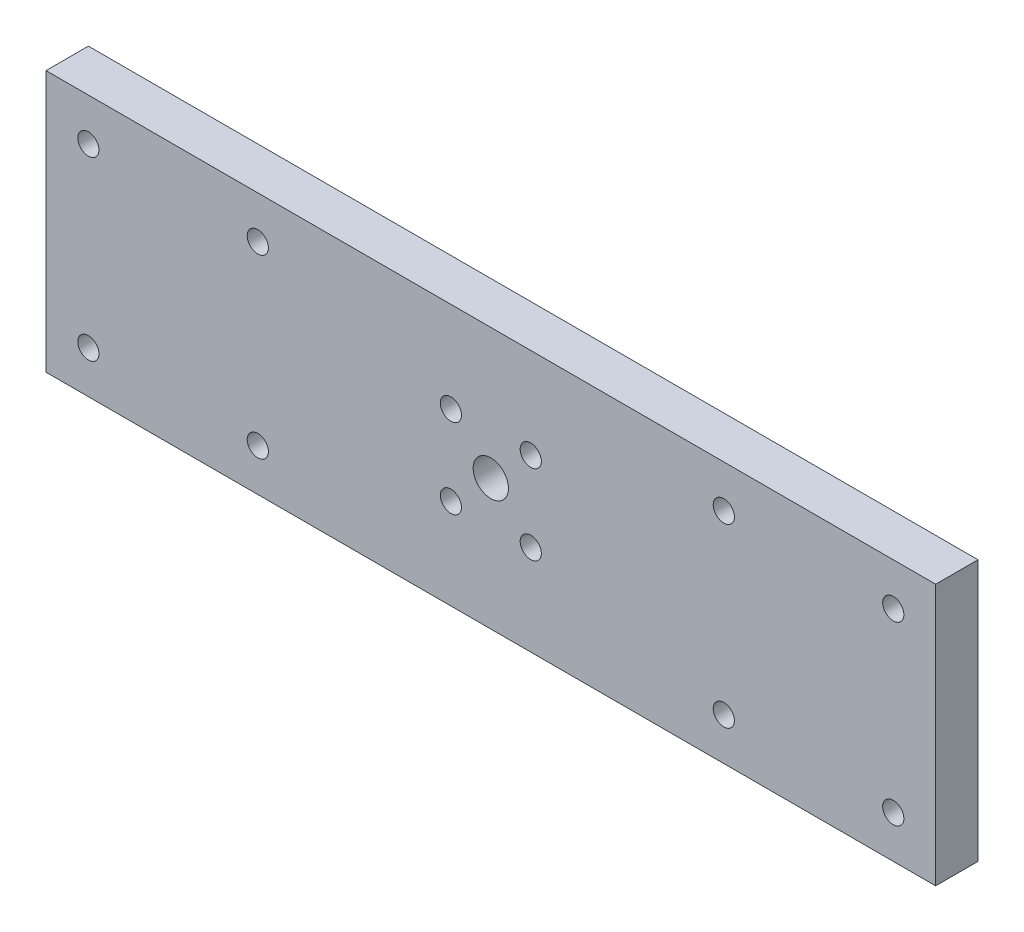
SolidWorks part; units mm, degrees
ref_plane "前视基准面" through (0, 0, 0) normal (0, 0, 1) x (1, 0, 0)
ref_plane "上视基准面" through (0, 0, 0) normal (0, 1, 0) x (1, 0, 0)
ref_plane "右视基准面" through (0, 0, 0) normal (1, 0, 0) x (0, 0, -1)
sketch "草图1" plane through (0, 0, 0) normal (0, 0, 1) x (1, 0, 0)
  line L1 (-63, 18.5) -> (63, 18.5)
  line L2 (-63, 18.5) -> (-63, -18.5)
  line L3 (-63, -18.5) -> (63, -18.5)
  line L4 (63, 18.5) -> (63, -18.5)
  line L5 (-63, 18.5) -> (63, -18.5) construction
  line L6 (-63, -18.5) -> (63, 18.5) construction
  line L7 (-57, 12.5) -> (-33, 12.5)
  line L8 (-57, 12.5) -> (-57, -12.5)
  line L9 (-57, -12.5) -> (-33, -12.5)
  line L10 (-33, 12.5) -> (-33, -12.5)
  line L11 (-57, 12.5) -> (-33, -12.5) construction
  line L12 (-57, -12.5) -> (-33, 12.5) construction
  line L13 (33, 12.5) -> (57, 12.5)
  line L14 (33, 12.5) -> (33, -12.5)
  line L15 (33, -12.5) -> (57, -12.5)
  line L16 (57, 12.5) -> (57, -12.5)
  line L17 (33, 12.5) -> (57, -12.5) construction
  line L18 (33, -12.5) -> (57, 12.5) construction
  line L19 (-10, 10) -> (10, 10)
  line L20 (-10, 10) -> (-10, -10)
  line L21 (-10, -10) -> (10, -10)
  line L22 (10, 10) -> (10, -10)
  line L23 (-10, 10) -> (10, -10) construction
  line L24 (-10, -10) -> (10, 10) construction
  circle A0 centre (-57, 12.5) radius 1.5
  circle A1 centre (-33, 12.5) radius 1.5
  circle A2 centre (-57, -12.5) radius 1.5
  circle A3 centre (-33, -12.5) radius 1.5
  circle A4 centre (33, 12.5) radius 1.5
  circle A5 centre (57, 12.5) radius 1.5
  circle A6 centre (57, -12.5) radius 1.5
  circle A7 centre (33, -12.5) radius 1.5
  circle A8 centre (0, 0) radius 8
  circle A9 centre (-5.6569, 5.6569) radius 1.5
  circle A10 centre (5.6569, 5.6569) radius 1.5
  circle A11 centre (-5.6569, -5.6569) radius 1.5
  circle A12 centre (5.6569, -5.6569) radius 1.5
  circle A13 centre (0, 0) radius 2.5
  point P0 (0, 0)
  point P6 (-45, 0)
  point P11 (45, 0)
  dimension "D5" = 3
  dimension "D8" = 16
  dimension "D9" = 3
  dimension "D11" = 5
  dimension "D1" = 24
  dimension "D2" = 33
  dimension "D3" = 33
  dimension "D4" = 25
  dimension "D6" = 6
  dimension "D7" = 6
  dimension "D10" = 20
extrude "凸台-拉伸1" add sketch "草图1" along normal blind 6 contours L4 L1 L2 L3 A7 L14 A4 L13 A5 L16 A6 L15 A3 L9 A2 L8 A0 L7 A1 L10 L19 L22 L21 L20 | A3 L10 A1 L7 A0 L8 A2 L9 | A7 L15 A6 L16 A5 L13 A4 L14 | L22 L19 L20 L21 A12 A8 A11 A9 A10 | A12 A8 A10 A9 A11 A13
